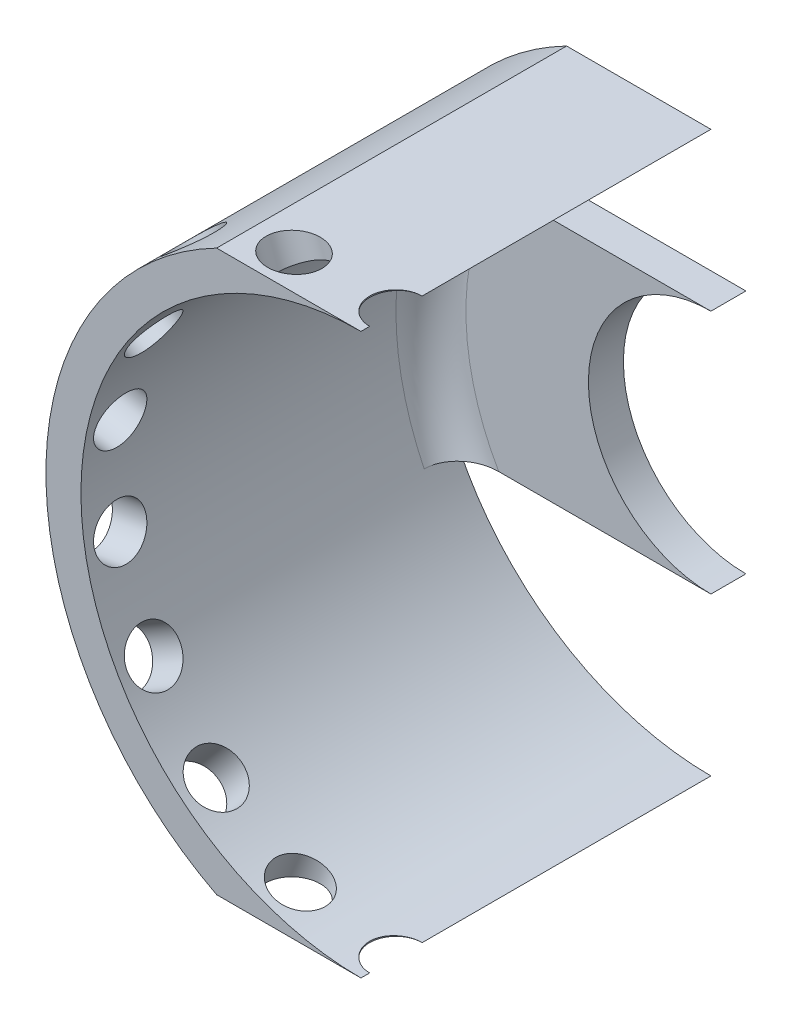
SolidWorks part; units mm, degrees
material "ABS"
ref_plane "Спереди" through (0, 0, 0) normal (0, 0, 1) x (1, 0, 0)
ref_plane "Сверху" through (0, 0, 0) normal (0, 1, 0) x (1, 0, 0)
ref_plane "Справа" through (0, 0, 0) normal (1, 0, 0) x (0, 0, -1)
sketch "Эскиз1" plane through (0, 0, 0) normal (0, 0, 1) x (1, 0, 0)
  line L0 (0, 3.5) -> (-8.2916, 3.5)
  line L1 (0, -3.5) -> (-8.2916, -3.5)
  arc A0 (0, 3.5) -> (0, -3.5) centre (0, 0) ccw
  arc A1 (-8.2916, 3.5) -> (-8.2916, -3.5) centre (0, 0) ccw
  dimension "D1" = 3.5
  dimension "D2" = 9
  dimension "D3" = 180
extrude "Бобышка-Вытянуть1" add sketch "Эскиз1" along normal blind 1
sketch "Эскиз2" plane through (0, 0, 1) normal (0, 0, 1) x (1, 0, 0)
  line L0 (0, 8) -> (-4.1231, 8)
  line L1 (0, -8) -> (-4.1231, -8)
  arc A0 (-4.1231, 8) -> (-4.1231, -8) centre (0, 0) ccw
  arc A1 (0, 8) -> (0, -8) centre (0, 0) ccw
  dimension "D1" = 9
  dimension "D2" = 1
  dimension "D3" = 16
  dimension "D4" = 16
extrude "Бобышка-Вытянуть2" add sketch "Эскиз2" along normal blind 10
sketch "Эскиз3" plane through (0, 0, 0) normal (0, 1, 0) x (1, 0, 0)
  line L1 (0, 0) -> (0, 50000) construction
  circle A0 centre (0, -10) radius 0.75
  dimension "D2" = 1.5
  dimension "D1" = 10
extrude "Вырез-Вытянуть1" cut sketch "Эскиз3" against normal blind 10
pattern_circular "Круговой массив1" count 18 over 360 about axis through (0, 0, 0) along (0, 0, -1) of "Вырез-Вытянуть1"
fillet "Скругление1" radius 1 1 edges at (-8, 0, 1)
